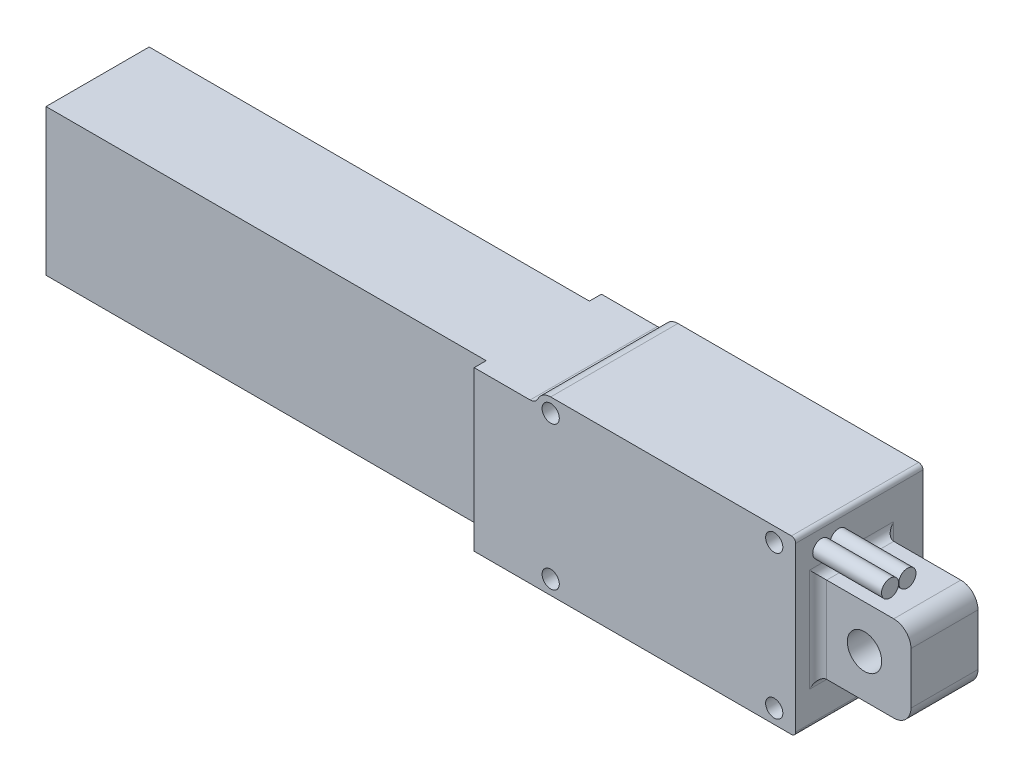
SolidWorks part; units mm, degrees
ref_plane "Plan de face" through (0, 0, 0) normal (0, 0, 1) x (1, 0, 0)
ref_plane "Plan de dessus" through (0, 0, 0) normal (0, 1, 0) x (1, 0, 0)
ref_plane "Plan de droite" through (0, 0, 0) normal (1, 0, 0) x (0, 0, -1)
sketch "Esquisse1" plane through (0, 0, 0) normal (0, 0, 1) x (1, 0, 0)
  line L1 (-18.7, 10) -> (18.7, 10)
  line L2 (-18.7, 10) -> (-18.7, -10)
  line L3 (-18.7, -10) -> (18.7, -10)
  line L4 (18.7, 10) -> (18.7, -10)
  line L5 (-18.7, 10) -> (18.7, -10) construction
  line L6 (-18.7, -10) -> (18.7, 10) construction
  point P0 (0, 0)
  dimension "D1" = 20
  dimension "D2" = 37.4
extrude "Boss.-Extru.1" add sketch "Esquisse1" along normal blind 14.8
sketch "Esquisse2" plane through (0, 0, 14.8) normal (0, 0, 1) x (1, 0, 0)
  line L0 (-24.1, 0) -> (24.1, 0) construction
  line L2 (18.7, -10) -> (18.7, 10) construction
  line L3 (27.5, 5) -> (18.7, 5) construction
  line L4 (29.5, 3) -> (29.5, -3)
  line L5 (27.5, -5) -> (18.7, -5) construction
  line L6 (18.7, 5) -> (18.7, -5)
  line L7 (29.5, 5) -> (18.7, -5) construction
  line L8 (29.5, -5) -> (18.7, 5) construction
  line L9 (18.7, -6) -> (18.7, 6)
  line L10 (19.7, 5) -> (27.5, 5)
  line L11 (19.7, -5) -> (27.5, -5)
  circle A0 centre (24.1, 0) radius 2
  arc A1 (27.5, 5) -> (29.5, 3) centre (27.5, 3) cw
  arc A2 (29.5, -3) -> (27.5, -5) centre (27.5, -3) cw
  arc A3 (18.7, 6) -> (19.7, 5) centre (19.7, 6) ccw
  arc A4 (18.7, -6) -> (19.7, -5) centre (19.7, -6) cw
  point P4 (0, 0)
  line M12 (18.7, -10) -> (18.7, 10)
  dimension "D2" = 4
  dimension "D4" = 2
  dimension "2" = 1
  dimension "D1" = 7.8
  dimension "D3" = 10
extrude "Boss.-Extru.2" add sketch "Esquisse2" against normal blind 7.8 from offset 2.6 contours A4 L11 A2 L4 A1 L10 A3 A0 M12 offset against normal yes
sketch "Esquisse4" plane through (0, 0, 14.8) normal (0, 0, 1) x (1, 0, 0)
  line L0 (-24.1, 0) -> (24.1, 0) construction
  line L1 (-18.7, 10) -> (-18.7, -10) construction
  line L2 (-69.9, 8.5) -> (-18.7, 8.5)
  line L3 (-69.9, 8.5) -> (-69.9, -8.5)
  line L4 (-69.9, -8.5) -> (-18.7, -8.5)
  line L5 (-18.7, 8.5) -> (-18.7, -8.5)
  line L6 (-69.9, 8.5) -> (-18.7, -8.5) construction
  line L7 (-69.9, -8.5) -> (-18.7, 8.5) construction
  line L8 (-18.7, -10) -> (18.7, -10) construction
  point P0 (-44.3, 0)
  point P4 (0, 0)
  point P14 (24.6, 0)
  dimension "D1" = 1.5
  dimension "D2" = 94
extrude "Boss.-Extru.3" add sketch "Esquisse4" against normal blind 12 from offset 1.4 offset against normal yes
sketch "Esquisse7" plane through (-69.9, 0, 0) normal (-1, 0, 0) x (0, 0, 1)
  line L0 (1.4, 8.5) -> (13.4, -8.5) construction
  line L1 (1.4, -8.5) -> (13.4, 8.5) construction
  line L3 (2.9, 4.5) -> (11.9, 4.5)
  line L4 (2.9, 4.5) -> (2.9, -4.5)
  line L5 (2.9, -4.5) -> (11.9, -4.5)
  line L6 (11.9, 4.5) -> (11.9, -4.5)
  line L7 (2.9, 4.5) -> (11.9, -4.5) construction
  line L8 (2.9, -4.5) -> (11.9, 4.5) construction
  point P8 (7.4, 0)
  dimension "D1" = 9
  dimension "D2" = 9
extrude "Enlèv. mat.-Extru.1" cut sketch "Esquisse7" against normal blind 50
fillet "Congé1" radius 1 3 edges at (18.9929, -5.2929, 4.4) (18.7, 0, 4.4) (18.9929, 5.2929, 4.4)
fillet "Congé2" radius 1 3 edges at (18.7, 0, 12.2) (18.9929, 5.2929, 12.2) (18.9929, -5.2929, 12.2)
sketch "Esquisse10" plane through (0, 0, 14.8) normal (0, 0, 1) x (1, 0, 0)
  line L0 (-18.7, 0) -> (24.1, 0) construction
  line L1 (-18.7, -8.5) -> (-18.7, 8.5) construction
  line L2 (18.7, -6) -> (18.7, 6) construction
  line L3 (16.2, 8.35) -> (-9.8, 8.35) construction
  line L4 (-18.7, 8.5) -> (-12.1875, 8.5)
  line L5 (18.7, 10) -> (-18.7, 10) construction
  line L10 (18.7, -10) -> (18.7, 10)
  line L11 (18.7, 10) -> (-18.7, 10)
  line L12 (-18.7, 10) -> (-18.7, -10)
  line L13 (-18.7, -10) -> (18.7, -10)
  line L15 (-9.8, 10) -> (-18.7, 10)
  line L16 (-18.7, 10) -> (-18.7, 8.5)
  circle A0 centre (16.2, 8.35) radius 1
  circle A1 centre (-9.8, 8.35) radius 1
  arc A2 (-9.8, 10) -> (-11.2865, 9.066) centre (-9.8, 8.35) ccw
  arc A3 (-12.1875, 8.5) -> (-11.2865, 9.066) centre (-12.1875, 9.5) ccw
  circle A4 centre (-9.8, -8.35) radius 1
  circle A5 centre (16.2, -8.35) radius 1
  point P14 (0, 0)
  dimension "D2" = 2
  dimension "D5" = 2
  dimension "D6" = 0
  dimension "D7" = 1
  dimension "D1" = 8.35
  dimension "D3" = 2.5
  dimension "D4" = 26
extrude "Enlèv. mat.-Extru.2" cut sketch "Esquisse10" against normal through all
fillet "Congé3" radius 0.5 2 edges at (18.7, -10, 7.4) (18.7, 10, 7.4)
sketch "Esquisse11" plane through (18.7, 0, 0) normal (1, 0, 0) x (0, 0, -1)
  line L0 (0, 9.5) -> (-14.8, 9.5) construction
  circle A0 centre (-11.8216, 7.5) radius 1
  circle A1 centre (-9.8116, 7.5) radius 1
  dimension "D1" = 2
  dimension "D4" = 2
  dimension "D2" = 2
  dimension "D3" = 2.01
extrude "Boss.-Extru.5" add sketch "Esquisse11" along normal blind 8
